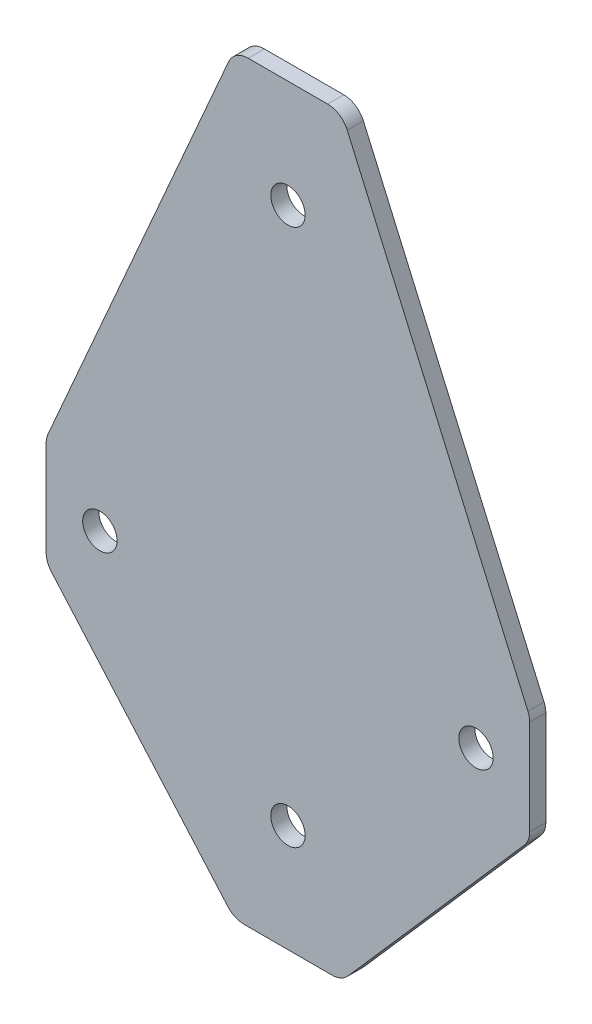
SolidWorks part; units mm, degrees
material "5052-H34"
ref_plane "正面" through (0, 0, 0) normal (0, 0, 1) x (1, 0, 0)
ref_plane "平面" through (0, 0, 0) normal (0, 1, 0) x (1, 0, 0)
ref_plane "右側面" through (0, 0, 0) normal (1, 0, 0) x (0, 0, -1)
sketch "ｽｹｯﾁ1" plane through (0, 0, 0) normal (0, 0, 1) x (1, 0, 0)
  line L0 (0, 0) -> (0, 50) construction
  line L1 (0, 15) -> (-17.5, 15) construction
  line L2 (-5, 60) -> (-22.5, 20)
  line L3 (-5, 60) -> (5, 60)
  line L4 (-5, 10) -> (-5, -10) construction
  line L5 (-5, -10) -> (5, -10)
  line L6 (5, 60) -> (5, 20) construction
  line L7 (-5, 60) -> (5, -10) construction
  line L8 (-5, -10) -> (5, 60) construction
  line L9 (0, 20) -> (5, 20) construction
  line L10 (-22.5, 20) -> (-22.5, 10)
  line L11 (5, 10) -> (22.5, 10) construction
  line L12 (22.5, 20) -> (22.5, 10)
  line L13 (-22.5, 20) -> (22.5, 10) construction
  line L14 (-22.5, 10) -> (22.5, 20) construction
  line L15 (-22.5, 10) -> (-5, -10)
  line L16 (22.5, 10) -> (5, -10)
  line L17 (5, 60) -> (22.5, 20)
  line L18 (-22.5, 20) -> (-5, 20) construction
  line L19 (-5, 60) -> (-5, 20) construction
  line L20 (-5, 20) -> (0, 20) construction
  line L21 (-5, 20) -> (-5, 16.1111) construction
  line L22 (-5, 16.1111) -> (-5, 15) construction
  line L23 (-5, 15) -> (-5, 13.8889) construction
  line L24 (-5, 13.8889) -> (-5, 10) construction
  line L25 (-22.5, 10) -> (-5, 10) construction
  line L26 (-5, 10) -> (-2.1429, 10) construction
  line L27 (-2.1429, 10) -> (0, 10) construction
  line L28 (0, 10) -> (2.1429, 10) construction
  line L29 (2.1429, 10) -> (5, 10) construction
  line L30 (5, 10) -> (5, -10) construction
  line L31 (5, 13.8889) -> (5, 10) construction
  line L32 (5, 16.1111) -> (5, 13.8889) construction
  line L33 (5, 20) -> (5, 16.1111) construction
  line L34 (5, 20) -> (22.5, 20) construction
  line L35 (0, 0) -> (0, -5) construction
  line L36 (0, -5) -> (-9.375, -5) construction
  circle A0 centre (0, 0) radius 1.6
  circle A1 centre (0, 50) radius 1.6
  circle A2 centre (-17.5, 15) radius 1.6
  circle A3 centre (17.5, 15) radius 1.6
  point P10 (0, 25)
  dimension "D1" = 3.2
  dimension "D2" = 50
  dimension "D4" = 3.2
  dimension "D3" = 15
  dimension "D5" = 35
  dimension "D6" = 10
  dimension "D7" = 10
  dimension "D8" = 45
  dimension "D9" = 70
  dimension "D11" = 5
extrude "ﾎﾞｽ - 押し出し1" add sketch "ｽｹｯﾁ1" along normal blind 1.5
fillet "ﾌｨﾚｯﾄ1" radius 2 8 edges at (-22.5, 20, 0.75) (-22.5, 10, 0.75) (-5, -10, 0.75) (5, -10, 0.75) (22.5, 10, 0.75) (22.5, 20, 0.75) (-5, 60, 0.75) (5, 60, 0.75)
